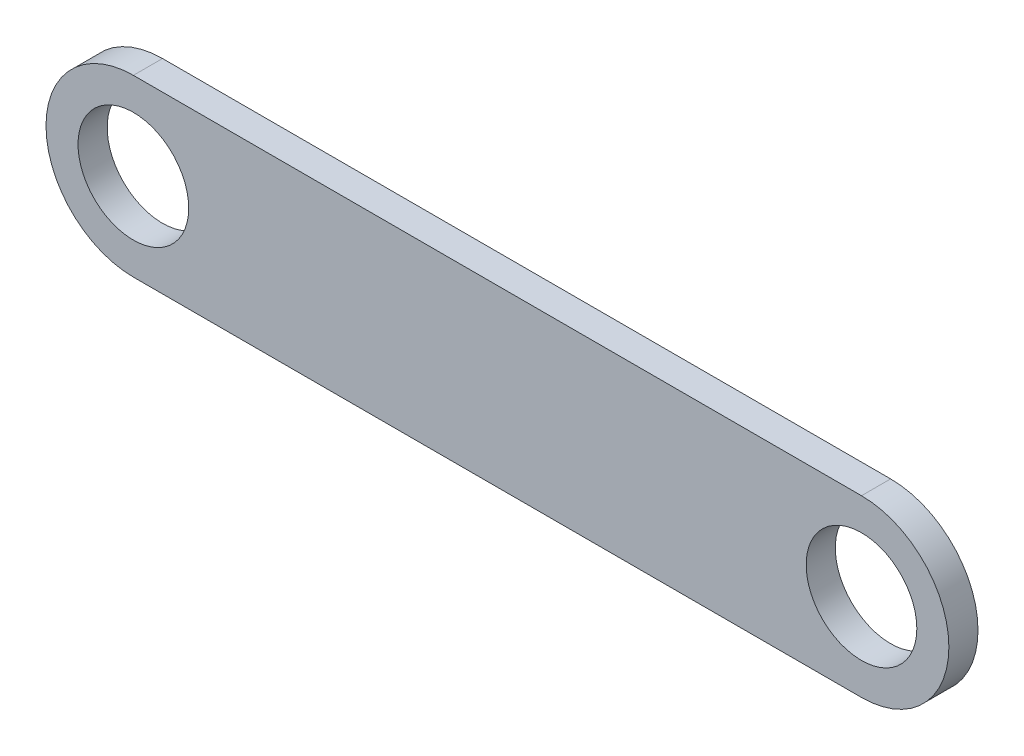
SolidWorks part; units mm, degrees
ref_plane "Front Plane" through (0, 0, 0) normal (0, 0, 1) x (1, 0, 0)
ref_plane "Top Plane" through (0, 0, 0) normal (0, 1, 0) x (1, 0, 0)
ref_plane "Right Plane" through (0, 0, 0) normal (1, 0, 0) x (0, 0, -1)
sketch "Sketch1" plane through (0, 0, 0) normal (0, 0, 1) x (1, 0, 0)
  line L0 (0, 0) -> (125, 0) construction
  line L1 (0, 15) -> (125, 15)
  line L2 (0, -15) -> (125, -15)
  arc A0 (0, 15) -> (0, -15) centre (0, 0) ccw
  arc A1 (125, -15) -> (125, 15) centre (125, 0) ccw
  circle A2 centre (0, 0) radius 9.5
  circle A3 centre (125, 0) radius 9.5
  point P3 (62.5, 0)
  dimension "D1" = 15
  dimension "D2" = 19
  dimension "D3" = 125
extrude "Boss-Extrude1" add sketch "Sketch1" along normal blind 5
